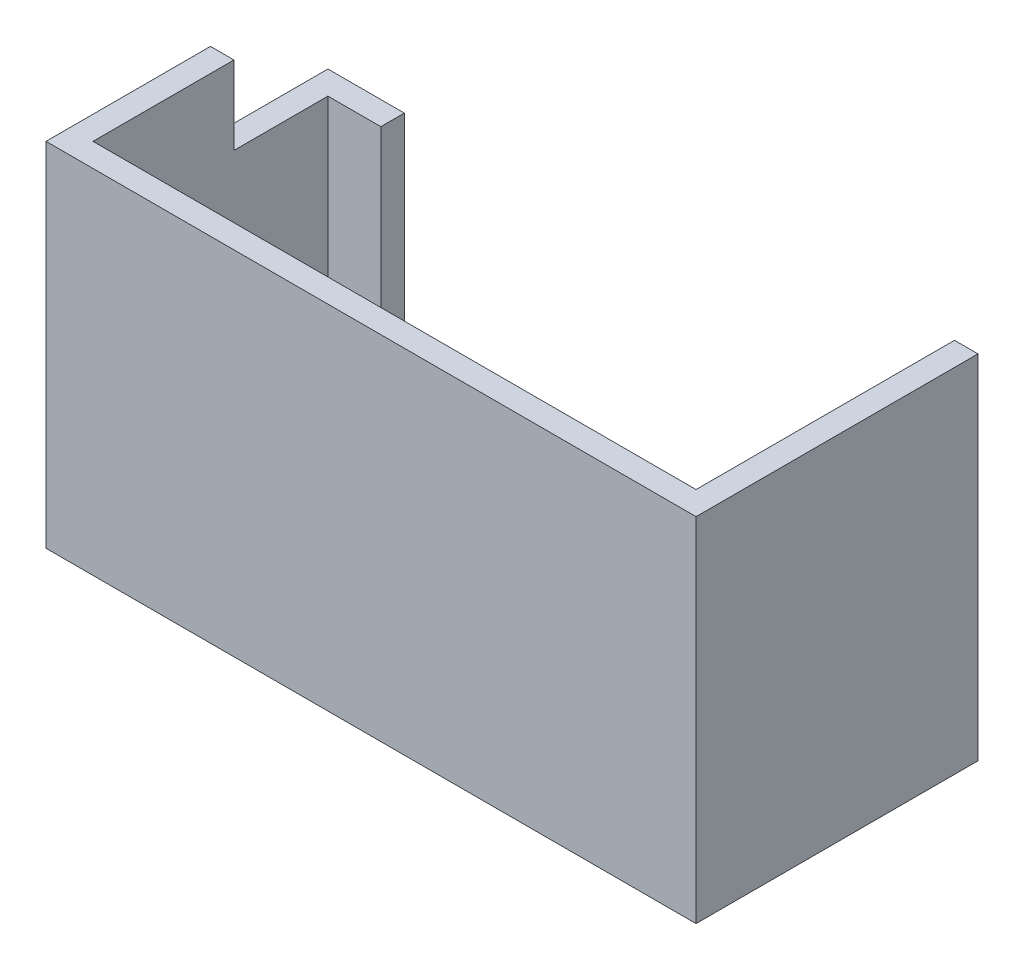
SolidWorks part; units mm, degrees
ref_plane "Front Plane" through (0, 0, 0) normal (0, 0, 1) x (1, 0, 0)
ref_plane "Top Plane" through (0, 0, 0) normal (0, 1, 0) x (1, 0, 0)
ref_plane "Right Plane" through (0, 0, 0) normal (1, 0, 0) x (0, 0, -1)
sketch "Sketch1" plane through (0, 0, 0) normal (0, 1, 0) x (1, 0, 0)
  line L0 (0, 30) -> (77, 0) construction
  line L1 (0, 0) -> (77, 0)
  line L2 (0, 0) -> (0, 30)
  line L3 (0, 30) -> (77, 30)
  line L4 (77, 0) -> (77, 30)
  line L5 (77, 30) -> (0, 0) construction
  line L6 (38.5, 30) -> (38.5, 33) construction
  line L7 (-3, -3) -> (80, -3)
  line L8 (-3, -3) -> (-3, 33)
  line L9 (-3, 33) -> (80, 33)
  line L10 (80, -3) -> (80, 33)
  line L11 (-3, -3) -> (80, 33) construction
  line L12 (-3, 33) -> (80, -3) construction
  line L14 (38.5, 0) -> (38.5, -3) construction
  line L16 (77, 15) -> (80, 15) construction
  line L18 (0, 15) -> (-3, 15) construction
  point P5 (38.5, 15)
  dimension "D1" = 30
  dimension "D2" = 77
  dimension "D3" = 3
extrude "Boss-Extrude1" add sketch "Sketch1" along normal blind 5
sketch "Sketch2" plane through (0, 5, 0) normal (0, 1, 0) x (1, 0, 0)
  line L4 (0, 30) -> (0, 0) construction
  line L5 (0, 0) -> (77, 0) construction
  line L6 (77, 0) -> (77, 30) construction
  line L7 (77, 30) -> (0, 30) construction
  line L8 (80, -3) -> (80, 33)
  line L9 (80, 33) -> (-3, 33)
  line L10 (-3, 33) -> (-3, -3)
  line L11 (-3, -3) -> (80, -3)
  line L12 (80, -3) -> (80, 33)
  line L13 (80, 33) -> (-3, 33) construction
  line L14 (-3, 33) -> (-3, -3)
  line L15 (-3, -3) -> (80, -3)
  line L16 (77, 0) -> (77, 30)
  line L17 (0, 0) -> (77, 0)
  line L18 (0, 30) -> (0, 0)
  line L19 (77, 30) -> (0, 30) construction
  line L20 (6.7523, 33) -> (6.7523, 30)
  line L21 (38.5, -3) -> (38.5, 33) construction
  line L22 (70.2477, 33) -> (70.2477, 30)
  line L23 (-3, 33) -> (6.7523, 33)
  line L24 (6.7523, 30) -> (0, 30)
  line L25 (70.2477, 30) -> (77, 30)
  line L26 (80, 33) -> (70.2477, 33)
  dimension "D1" = 0
extrude "Boss-Extrude2" add sketch "Sketch2" along normal blind 40
sketch "Sketch3" plane through (0, 0, 0) normal (0, -1, 0) x (1, 0, 0)
  line L8 (80, -33) -> (80, 3)
  line L9 (80, 3) -> (-3, 3)
  line L10 (-3, 3) -> (-3, -33)
  line L11 (-3, -33) -> (80, -33)
  line L12 (80, -33) -> (80, 3)
  line L13 (80, 3) -> (-3, 3)
  line L14 (-3, 3) -> (-3, -33)
  line L15 (-3, -33) -> (80, -33)
  dimension "D1" = 0
extrude "Boss-Extrude3" add sketch "Sketch3" against normal blind 1 contours L12 L13 L14 L15
sketch "Sketch4" plane through (0, 0, -33) normal (0, 0, -1) x (-1, 0, 0)
  line L0 (-6.7523, 45) -> (-6.7523, 5) construction
  line L1 (3, 0) -> (-6.7523, 0) construction
  line L2 (3, 0) -> (3, 35) construction
  line L3 (3, 35) -> (-6.7523, 35) construction
  line L4 (-6.7523, 0) -> (-6.7523, 35) construction
  line L6 (3, 35) -> (-6.7523, 35)
  line L7 (3, 35) -> (3, 45)
  line L8 (3, 45) -> (-6.7523, 45)
  line L9 (-6.7523, 35) -> (-6.7523, 45)
  dimension "D1" = 35
extrude "Cut-Extrude1" cut sketch "Sketch4" against normal blind 15
sketch "Sketch5" plane through (0, 0, -33) normal (0, 0, -1) x (-1, 0, 0)
  line L0 (-70.2477, 45) -> (-70.2477, 5) construction
  line L1 (-80, 0) -> (-70.2477, 0) construction
  line L2 (-80, 0) -> (-80, 24.4) construction
  line L3 (-80, 24.4) -> (-70.2477, 24.4) construction
  line L4 (-70.2477, 0) -> (-70.2477, 24.4) construction
  line L5 (-80, 30.6) -> (-73.8, 24.4) construction
  line L6 (-80, 24.4) -> (-73.8, 24.4) construction
  line L7 (-80, 24.4) -> (-80, 30.6) construction
  line L8 (-80, 30.6) -> (-73.8, 30.6) construction
  line L9 (-73.8, 24.4) -> (-73.8, 30.6) construction
  line L10 (-73.8, 30.6) -> (-80, 24.4) construction
  line L11 (-76.9, 27.5) -> (-76.9, 0) construction
  line L12 (-77, 24.4) -> (-69.5994, 24.4)
  line L13 (-69.5994, 24.4) -> (-69.5994, 45.6886)
  line L14 (-77, 45.6886) -> (-69.5994, 45.6886)
  line L15 (-77, 24.4) -> (-77, 45.6886)
  point P12 (0, 0)
  point P13 (0, 0)
  dimension "D1" = 6.2
  dimension "D2" = 27.5
extrude "Cut-Extrude2" cut sketch "Sketch5" against normal up to next
